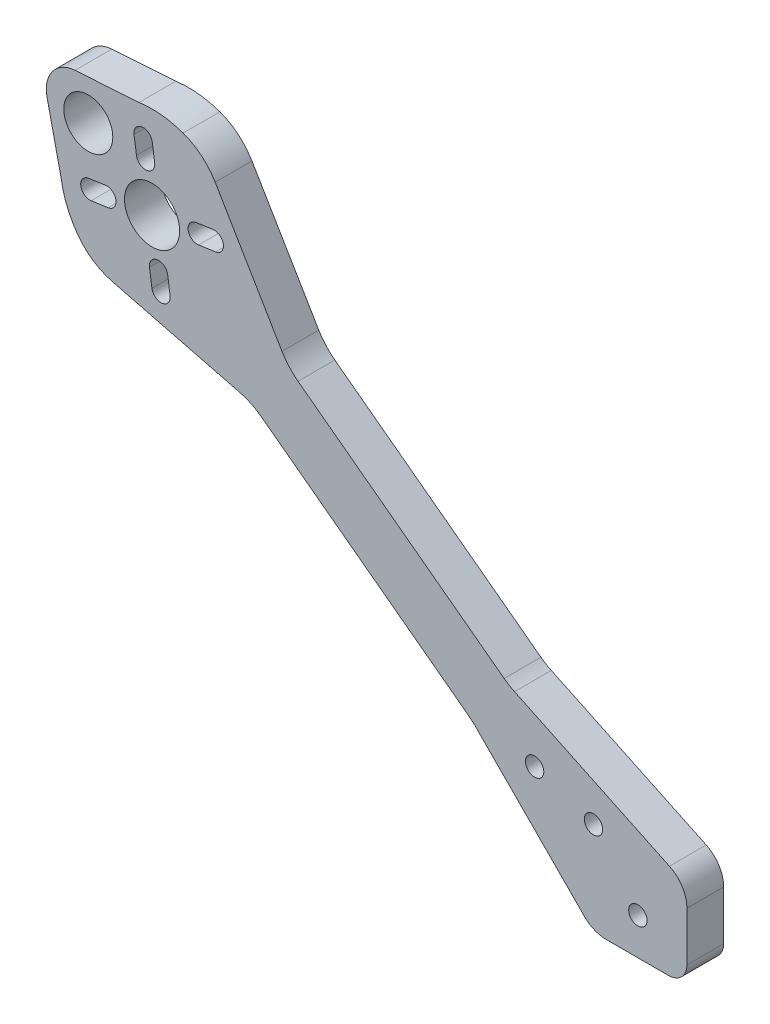
SolidWorks part; units mm, degrees
ref_plane "Alzado" through (0, 0, 0) normal (0, 0, 1) x (1, 0, 0)
ref_plane "Planta" through (0, 0, 0) normal (0, 1, 0) x (1, 0, 0)
ref_plane "Vista lateral" through (0, 0, 0) normal (1, 0, 0) x (0, 0, -1)
sketch "Croquis1" plane through (0, 0, 0) normal (0, 0, 1) x (1, 0, 0)
  line L0 (0, 0) -> (-105.6765, 79.0979) construction
  line L1 (8, 6) -> (-8, 6) construction
  line L2 (8, 6) -> (8, -6) construction
  line L3 (8, -6) -> (-8, -6) construction
  line L4 (-8, 6) -> (-8, -6) construction
  line L5 (8, 6) -> (-8, -6) construction
  line L6 (8, -6) -> (-8, 6) construction
  line L7 (24.85, 18.6) -> (-24.85, 18.6) construction
  line L8 (24.85, 18.6) -> (24.85, -18.6) construction
  line L9 (24.85, -18.6) -> (-24.85, -18.6) construction
  line L10 (-24.85, 18.6) -> (-24.85, -18.6) construction
  line L11 (24.85, 18.6) -> (-24.85, -18.6) construction
  line L12 (24.85, -18.6) -> (-24.85, 18.6) construction
  line L17 (-20.3743, -15.25) -> (20.3743, 15.25) construction
  line L18 (-20.3743, 15.25) -> (20.3743, -15.25) construction
  line L19 (0, 3) -> (0, 11.0059)
  line L20 (-3, 0) -> (-13.1644, 0)
  line L21 (-32.0232, 23.9691) -> (-29.027, 27.972) construction
  line L22 (-2.8522, 15.5211) -> (-28.1277, 27.5441)
  line L23 (-32.0232, 23.9691) -> (-35.0193, 19.9662) construction
  line L24 (-16.7174, 1.482) -> (-34.4983, 19.44)
  line L25 (-87.2632, 65.3157) -> (-88.9361, 76.946) construction
  line L31 (-90.4208, 76.7324) -> (-87.4514, 77.1596) construction
  line L32 (-87.4514, 77.1596) -> (-87.2378, 75.6748) construction
  line L33 (-89.595, 70.9915) -> (-86.6256, 71.4186) construction
  line L34 (-86.6256, 71.4186) -> (-86.8392, 72.9034) construction
  line L35 (-87.2378, 75.6748) -> (-86.8392, 72.9034)
  line L36 (-89.595, 70.9915) -> (-89.8086, 72.4762) construction
  line L37 (-90.4208, 76.7324) -> (-90.2073, 75.2477) construction
  line L38 (-90.2073, 75.2477) -> (-89.8086, 72.4762)
  line L39 (-76.904, 65.2903) -> (-79.6755, 64.8917)
  line L40 (-77.3312, 68.2598) -> (-80.1026, 67.8611)
  line L41 (-87.2632, 65.3157) -> (-75.6329, 66.9886) construction
  line L42 (-75.8464, 68.4734) -> (-75.4193, 65.5039) construction
  line L43 (-75.4193, 65.5039) -> (-76.904, 65.2903) construction
  line L44 (-81.5874, 67.6476) -> (-81.1602, 64.6781) construction
  line L45 (-81.1602, 64.6781) -> (-79.6755, 64.8917) construction
  line L46 (-81.5874, 67.6476) -> (-80.1026, 67.8611) construction
  line L47 (-75.8464, 68.4734) -> (-77.3312, 68.2598) construction
  line L48 (-87.2885, 54.9565) -> (-87.6872, 57.728)
  line L49 (-84.3191, 55.3837) -> (-84.7177, 58.1552)
  line L50 (-87.2632, 65.3157) -> (-85.5902, 53.6854) construction
  line L51 (-84.1055, 53.899) -> (-87.0749, 53.4718) construction
  line L52 (-87.0749, 53.4718) -> (-87.2885, 54.9565) construction
  line L53 (-84.9313, 59.6399) -> (-87.9007, 59.2127) construction
  line L54 (-87.9007, 59.2127) -> (-87.6872, 57.728) construction
  line L55 (-84.9313, 59.6399) -> (-84.7177, 58.1552) construction
  line L56 (-84.1055, 53.899) -> (-84.3191, 55.3837) construction
  line L57 (-97.6223, 65.341) -> (-94.8508, 65.7397)
  line L58 (-97.1952, 62.3716) -> (-94.4237, 62.7703)
  line L59 (-87.2632, 65.3157) -> (-98.8935, 63.6427) construction
  line L60 (-98.6799, 62.158) -> (-99.107, 65.1275) construction
  line L61 (-99.107, 65.1275) -> (-97.6223, 65.341) construction
  line L62 (-92.939, 62.9838) -> (-93.3661, 65.9533) construction
  line L63 (-93.3661, 65.9533) -> (-94.8508, 65.7397) construction
  line L64 (-92.939, 62.9838) -> (-94.4237, 62.7703) construction
  line L65 (-98.6799, 62.158) -> (-97.1952, 62.3716) construction
  line L66 (-87.2632, 65.3157) -> (-96.2516, 53.307) construction
  line L67 (-98.8935, 63.6427) -> (-102.1104, 63.18) construction
  line L68 (-104.3993, 73.3969) -> (-102.1104, 63.18)
  line L69 (-85.5902, 53.6854) -> (-85.1275, 50.4685) construction
  line L74 (-99.8467, 79.4793) -> (-89.3988, 80.1629)
  line L75 (-95.0628, 64.9082) -> (-92.0666, 68.9111) construction
  line L76 (-15.25, 15.25) -> (15.25, 15.25) construction
  line L77 (-15.25, 15.25) -> (-15.25, -15.25) construction
  line L78 (-15.25, -15.25) -> (15.25, -15.25) construction
  line L79 (15.25, 15.25) -> (15.25, -15.25) construction
  line L80 (-15.25, 15.25) -> (15.25, -15.25) construction
  line L81 (-15.25, -15.25) -> (15.25, 15.25) construction
  line L82 (-93.7558, 52.6757) -> (-72.9843, 47.4218)
  line L83 (-76.9656, 75.1077) -> (-66.0702, 56.6592)
  line L84 (-63.452, 53.7387) -> (-63.1711, 53.5284)
  line L85 (-63.1711, 53.5284) -> (-29.8244, 28.5687)
  line L86 (-69.4442, 45.7329) -> (-35.6121, 20.4099)
  circle A0 centre (-24.85, 18.6) radius 1.5
  circle A2 centre (-8, 6) radius 1.5
  circle A12 centre (-97.6707, 73.1056) radius 4
  circle A13 centre (-87.2632, 65.3157) radius 4.5
  arc A16 (-90.2073, 75.2477) -> (-87.2378, 75.6748) centre (-88.7225, 75.4613) cw
  arc A17 (-86.8392, 72.9034) -> (-89.8086, 72.4762) centre (-88.3239, 72.6898) cw
  arc A18 (-77.3312, 68.2598) -> (-76.904, 65.2903) centre (-77.1176, 66.7751) cw
  arc A19 (-79.6755, 64.8917) -> (-80.1026, 67.8611) centre (-79.8891, 66.3764) cw
  arc A20 (-84.3191, 55.3837) -> (-87.2885, 54.9565) centre (-85.8038, 55.1701) cw
  arc A21 (-87.6872, 57.728) -> (-84.7177, 58.1552) centre (-86.2025, 57.9416) cw
  arc A22 (-97.1952, 62.3716) -> (-97.6223, 65.341) centre (-97.4087, 63.8563) cw
  arc A23 (-94.8508, 65.7397) -> (-94.4237, 62.7703) centre (-94.6373, 64.255) cw
  circle A24 centre (-87.2632, 65.3157) radius 15 construction
  arc A25 (-102.1104, 63.18) -> (-99.3845, 56.4798) centre (-87.2632, 65.3157) ccw
  arc A27 (-99.8467, 79.4793) -> (-104.3993, 73.3969) centre (-99.5202, 74.49) ccw
  arc A28 (-35.6121, 20.4099) -> (-34.4983, 19.44) centre (-41.6044, 12.4041) cw
  arc A29 (-29.8244, 28.5687) -> (-28.1277, 27.5441) centre (-23.8321, 36.5745) ccw
  arc A34 (-13.1644, 0) -> (-16.7174, 1.482) centre (-13.1644, 5) cw
  arc A35 (0, 11.0059) -> (-2.8522, 15.5211) centre (-5, 11.0059) ccw
  arc A36 (0, 3) -> (-3, 0) centre (-3, 3) cw
  circle A37 centre (-15.25, 15.25) radius 1.5
  arc A38 (-72.9843, 47.4218) -> (-69.4442, 45.7329) centre (-75.4365, 37.7271) cw
  arc A39 (-93.7558, 52.6757) -> (-99.3845, 56.4798) centre (-91.3036, 62.3704) cw
  arc A40 (-89.3988, 80.1629) -> (-82.202, 79.436) centre (-87.2632, 65.3157) cw
  arc A41 (-76.9656, 75.1077) -> (-82.202, 79.436) centre (-85.5761, 70.0225) ccw
  arc A42 (-66.0702, 56.6592) -> (-63.452, 53.7387) centre (-57.4597, 61.7445) ccw
  point P0 (0, 0)
  point P6 (0, 0)
  point P11 (0, 0)
  point P85 (-87.2632, 65.3157)
  point P104 (-72.416, 67.4514)
  point P107 (-89.0705, 72.9139)
  point P110 (-95.0628, 64.9082)
  point P112 (-103.5231, 77.4861)
  point P113 (-88.1103, 71.2051)
  point P116 (-15.25, 0)
  point P119 (0, 14.1644)
  dimension "D6" = 69
  dimension "D9" = 10
  dimension "D10" = 13
  dimension "D15" = 10
  dimension "D14" = 5
  dimension "D16" = 5
  dimension "D17" = 3
  dimension "D20" = 10
  dimension "D25" = 8
  dimension "D26" = 9
  dimension "D1" = 16
  dimension "D2" = 12
  dimension "D3" = 49.7
  dimension "D4" = 37.2
  dimension "D5" = 40.7487
  dimension "D7" = 15.25
  dimension "D8" = 40
  dimension "D11" = 45
  dimension "D12" = 4
  dimension "D13" = 2.6898
  dimension "D18" = 30.5
  dimension "D19" = 30.5
  dimension "D21" = 5.95
  dimension "D22" = 2.8
  dimension "D23" = 5.8
  dimension "D24" = 3
extrude "Saliente-Extruir1" add sketch "Croquis1" along normal blind 6
